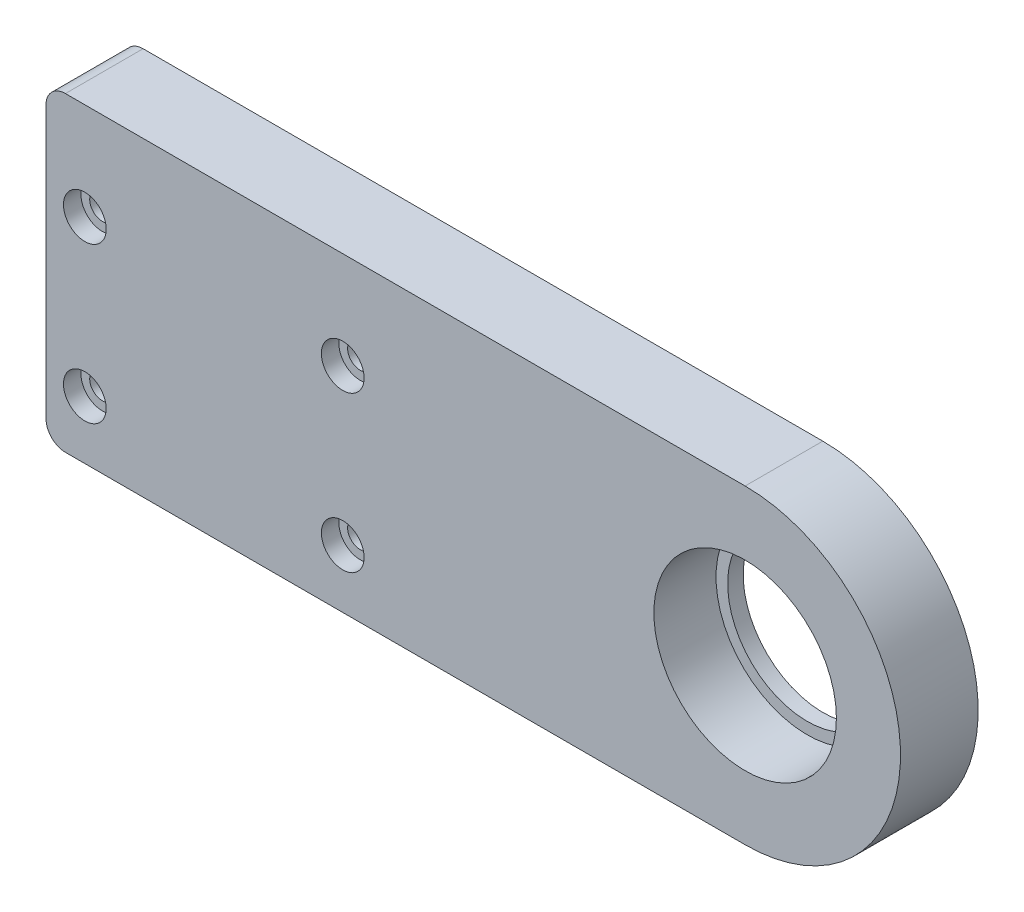
SolidWorks part; units mm, degrees
material "5052-H32"
ref_plane "Front Plane" through (0, 0, 0) normal (0, 0, 1) x (1, 0, 0)
ref_plane "Top Plane" through (0, 0, 0) normal (0, 1, 0) x (1, 0, 0)
ref_plane "Right Plane" through (0, 0, 0) normal (1, 0, 0) x (0, 0, -1)
sketch "Sketch1" plane through (0, 0, 0) normal (0, 0, 1) x (1, 0, 0)
  line L0 (0, 40) -> (-180, 40)
  line L1 (-180, 40) -> (-180, -40)
  line L2 (-180, -40) -> (0, -40)
  arc A1 (0, -40) -> (0, 40) centre (0, 0) ccw
  circle A2 centre (0, 0) radius 20.5
  dimension "D2" = 41
  dimension "D1" = 80
  dimension "D3" = 180
  dimension "D4" = 0
extrude "Boss-Extrude1" add sketch "Sketch1" along normal blind 20
sketch "Sketch2" plane through (0, 0, 20) normal (0, 0, 1) x (1, 0, 0)
  circle A0 centre (0, 0) radius 23.5
  dimension "D1" = 47
extrude "Cut-Extrude1" cut sketch "Sketch2" against normal blind 16
sketch "Sketch4" plane through (0, 0, 0) normal (0, 0, -1) x (-1, 0, 0)
  line L0 (180, 40) -> (180, -40) construction
  line L1 (180, -29) -> (95, -29)
  line L2 (180, -29) -> (180, -21)
  line L3 (180, -21) -> (95, -21)
  line L4 (95, -29) -> (95, -21)
  line L6 (180, 11) -> (95, 11)
  line L7 (180, 11) -> (180, 19)
  line L8 (180, 19) -> (95, 19)
  line L9 (95, 11) -> (95, 19)
  point P10 (180, 15)
  point P11 (180, -25)
  point P12 (95, 15)
  dimension "D1" = 8
  dimension "D2" = 8
  dimension "D3" = 40
  dimension "D4" = 15
  dimension "D5" = 85
extrude "Boss-Extrude2" add sketch "Sketch4" along normal blind 3
sketch "Sketch3" plane through (0, 0, 20) normal (0, 0, 1) x (1, 0, 0)
  line L0 (-180, 40) -> (-180, -40) construction
  circle A0 centre (-103.6, 15) radius 3.25
  circle A1 centre (-170, 15) radius 3.25
  circle A2 centre (-170, -25) radius 3.25
  circle A3 centre (-103.6, -25) radius 3.25
  dimension "D5" = 6.5
  dimension "D1" = 40
  dimension "D2" = 15
  dimension "D3" = 10
  dimension "D4" = 66.4
extrude "Cut-Extrude2" cut sketch "Sketch3" against normal through all
sketch "Sketch5" plane through (0, 0, 20) normal (0, 0, 1) x (1, 0, 0)
  circle A0 centre (-170, 15) radius 5.5
  circle A1 centre (-103.6, 15) radius 5.5
  circle A2 centre (-103.6, -25) radius 5.5
  circle A3 centre (-170, -25) radius 5.5
  dimension "D1" = 11
extrude "Cut-Extrude3" cut sketch "Sketch5" against normal blind 4.5
fillet "Fillet1" radius 5 2 edges at (-180, 40, 10) (-180, -40, 10)
